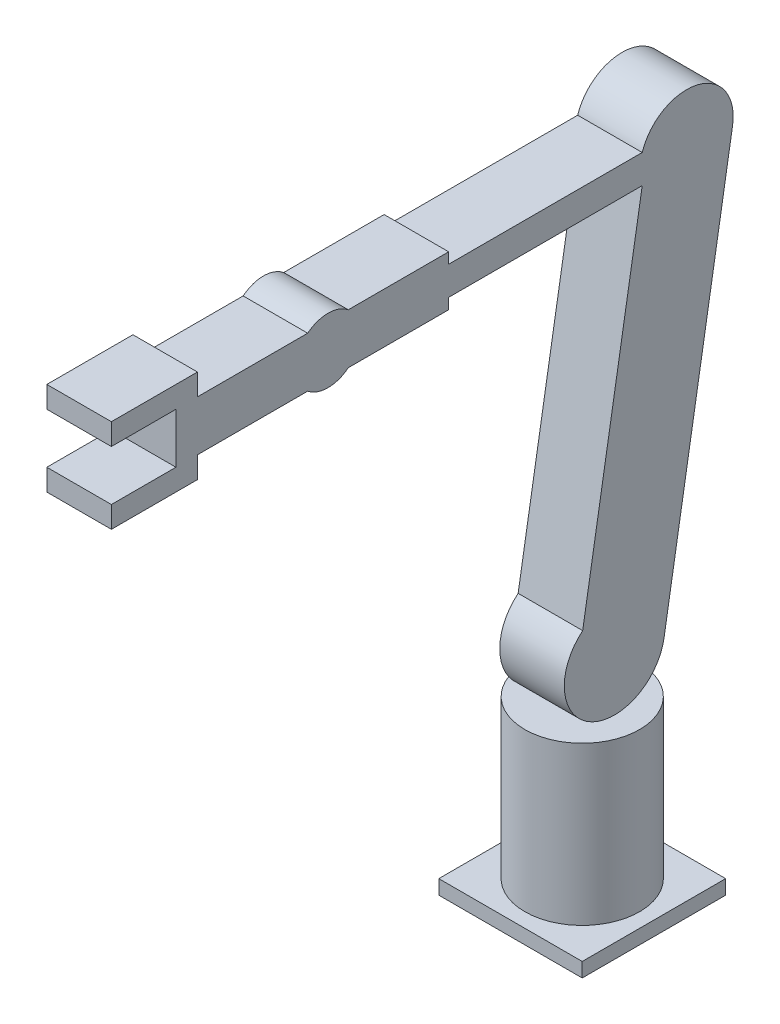
SolidWorks part; units mm, degrees
ref_plane "Front Plane" through (0, 0, 0) normal (0, 0, 1) x (1, 0, 0)
ref_plane "Top Plane" through (0, 0, 0) normal (0, 1, 0) x (1, 0, 0)
ref_plane "Right Plane" through (0, 0, 0) normal (1, 0, 0) x (0, 0, -1)
sketch "Sketch1" plane through (0, 0, 0) normal (0, 1, 0) x (1, 0, 0)
  circle A0 centre (0, 0) radius 40
  dimension "D1" = 80
extrude "Boss-Extrude1" add sketch "Sketch1" along normal blind 110
sketch "Sketch2" plane through (0, 0, 0) normal (0, -1, 0) x (1, 0, 0)
  line L1 (-50, 50) -> (50, 50)
  line L2 (-50, 50) -> (-50, -50)
  line L3 (-50, -50) -> (50, -50)
  line L4 (50, 50) -> (50, -50)
  line L5 (-50, 50) -> (50, -50) construction
  line L6 (-50, -50) -> (50, 50) construction
  point P0 (0, 0)
  dimension "D1" = 100
extrude "Boss-Extrude2" add sketch "Sketch2" along normal blind 10
sketch "Sketch3" plane through (0, 0, 0) normal (1, 0, 0) x (0, 0, -1)
  line L0 (0, 145) -> (50.2532, 430) construction
  line L1 (40, 110) -> (-40, 110) construction
  line L2 (50.2532, 430) -> (-199.7468, 430) construction
  line L3 (-199.7468, 430) -> (-290.7468, 430) construction
  line L4 (82.307, 424.6331) -> (34.5195, 139.2203)
  line L9 (-213.8889, 447.5) -> (-290.7468, 447.5)
  line L10 (-213.8889, 447.5) -> (-213.8889, 412.5)
  line L11 (-213.8889, 412.5) -> (-290.7468, 412.5)
  line L12 (-290.7468, 447.5) -> (-290.7468, 412.5)
  line L13 (-185.6047, 447.5) -> (-115.6047, 447.5)
  line L14 (-185.6047, 447.5) -> (-185.6047, 412.5)
  line L15 (-185.6047, 412.5) -> (-115.6047, 412.5)
  line L16 (-115.6047, 447.5) -> (-115.6047, 412.5)
  line L17 (-115.6047, 440) -> (19.3299, 440)
  line L18 (-115.6047, 440) -> (-115.6047, 420)
  line L19 (-115.6047, 420) -> (19.3299, 420)
  line L20 (19.3299, 440) -> (19.3299, 420)
  line L21 (34.5195, 139.2203) -> (-22.1811, 172.074)
  line L22 (-22.1811, 172.074) -> (19.3299, 420)
  line L23 (82.307, 424.6331) -> (19.3299, 420)
  line L25 (-305.7468, 462.5) -> (-290.7468, 462.5)
  line L26 (-305.7468, 462.5) -> (-305.7468, 397.5)
  line L27 (-305.7468, 397.5) -> (-290.7468, 397.5)
  line L28 (-290.7468, 462.5) -> (-290.7468, 397.5)
  line L29 (-290.7468, 462.5) -> (-350.7468, 462.5)
  line L30 (-290.7468, 462.5) -> (-290.7468, 447.5)
  line L31 (-290.7468, 447.5) -> (-350.7468, 447.5)
  line L32 (-350.7468, 462.5) -> (-350.7468, 447.5)
  line L33 (-290.7468, 397.5) -> (-350.7468, 397.5)
  line L34 (-290.7468, 397.5) -> (-290.7468, 412.5)
  line L35 (-290.7468, 412.5) -> (-350.7468, 412.5)
  line L36 (-350.7468, 397.5) -> (-350.7468, 412.5)
  circle A0 centre (50.2532, 430) radius 32.5
  circle A1 centre (0, 145) radius 35
  circle A2 centre (-199.7468, 430) radius 22.5
  point P29 (-305.7468, 430)
  dimension "D5" = 70
  dimension "D6" = 65
  dimension "D7" = 45
  dimension "D1" = 285
  dimension "D2" = 100
  dimension "D3" = 250
  dimension "D4" = 91
  dimension "D8" = 35
  dimension "D9" = 70
  dimension "D10" = 35
  dimension "D11" = 20
  dimension "D12" = 65
  dimension "D13" = 15
  dimension "D14" = 15
  dimension "D15" = 60
  dimension "D16" = 15
  dimension "D17" = 60
extrude "Boss-Extrude3" add sketch "Sketch3" along normal mid plane 45 separate body
